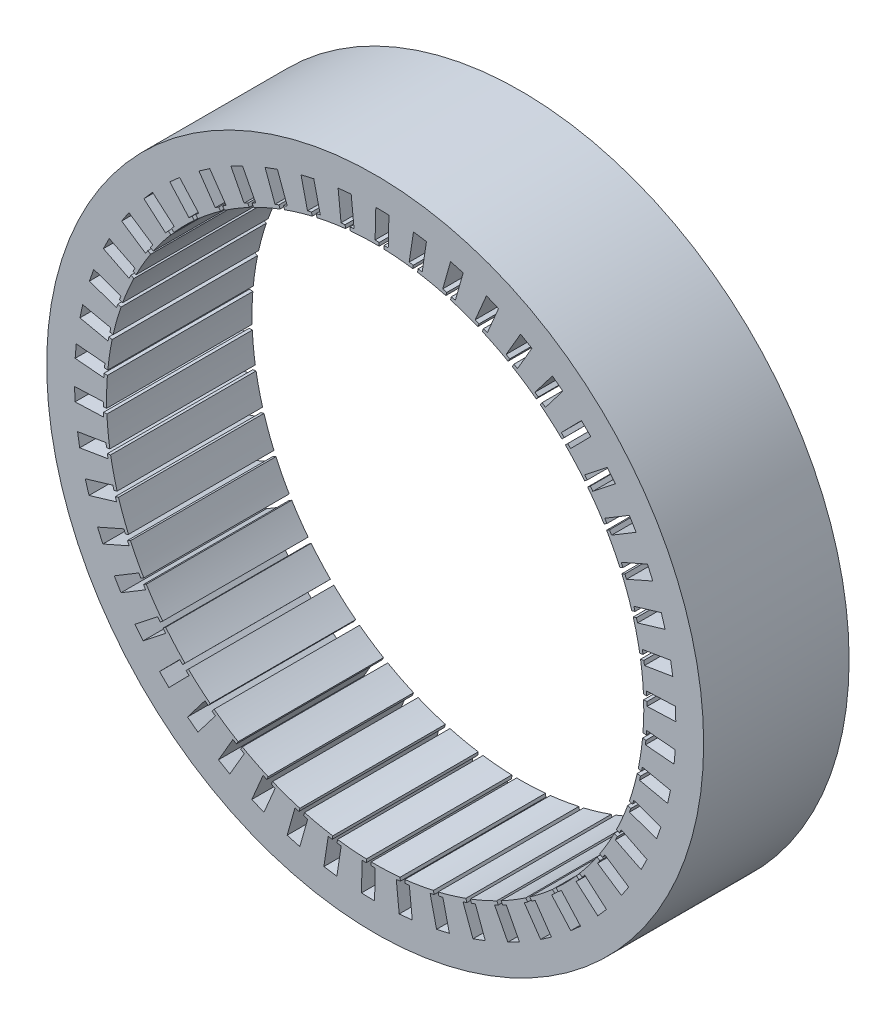
SolidWorks part; units mm, degrees
ref_plane "Спереди" through (0, 0, 0) normal (0, 0, 1) x (1, 0, 0)
ref_plane "Сверху" through (0, 0, 0) normal (0, 1, 0) x (1, 0, 0)
ref_plane "Справа" through (0, 0, 0) normal (1, 0, 0) x (0, 0, -1)
sketch "Эскиз1" plane through (0, 0, 0) normal (0, 0, 1) x (1, 0, 0)
  circle A0 centre (0, 0) radius 67.7538
  circle A1 centre (0, 0) radius 55.4
extrude "Rotor_stack" add sketch "Эскиз1" along normal blind 30 from offset 15
sketch "Эскиз2" plane through (0, 0, 0) normal (0, 0, 1) x (1, 0, 0)
  line L0 (54.5758, 1.6267) -> (56.0539, 1.6843)
  line L1 (56.0539, 1.6843) -> (56.0871, 0.8311)
  line L2 (56.0871, 0.8311) -> (62.0057, 1.0618)
  line L3 (62.0057, 1.0618) -> (61.9002, 3.7675)
  line L4 (61.9002, 3.7675) -> (55.9817, 3.5368)
  line L5 (55.9817, 3.5368) -> (56.0149, 2.6836)
  line L6 (56.0149, 2.6836) -> (54.5368, 2.626)
  line L7 (54.5368, 2.626) -> (54.5758, 1.6267)
  line L8 (53.9415, 8.4541) -> (55.4007, 8.6965)
  line L9 (55.4007, 8.6965) -> (55.5407, 7.8542)
  line L10 (55.5407, 7.8542) -> (61.3837, 8.8248)
  line L11 (61.3837, 8.8248) -> (60.9399, 11.4959)
  line L12 (60.9399, 11.4959) -> (55.0969, 10.5253)
  line L13 (55.0969, 10.5253) -> (55.2369, 9.683)
  line L14 (55.2369, 9.683) -> (53.7777, 9.4405)
  line L15 (53.7777, 9.4405) -> (53.9415, 8.4541)
  line L16 (52.4566, 15.1481) -> (53.8739, 15.5715)
  line L17 (53.8739, 15.5715) -> (54.1183, 14.7533)
  line L18 (54.1183, 14.7533) -> (59.7936, 16.4487)
  line L19 (59.7936, 16.4487) -> (59.0186, 19.0431)
  line L20 (59.0186, 19.0431) -> (53.3433, 17.3477)
  line L21 (53.3433, 17.3477) -> (53.5877, 16.5296)
  line L22 (53.5877, 16.5296) -> (52.1704, 16.1062)
  line L23 (52.1704, 16.1062) -> (52.4566, 15.1481)
  line L24 (50.1444, 21.6032) -> (51.4975, 22.2009)
  line L25 (51.4975, 22.2009) -> (51.8425, 21.4198)
  line L26 (51.8425, 21.4198) -> (57.2605, 23.8131)
  line L27 (57.2605, 23.8131) -> (56.1665, 26.2899)
  line L28 (56.1665, 26.2899) -> (50.7484, 23.8966)
  line L29 (50.7484, 23.8966) -> (51.0934, 23.1156)
  line L30 (51.0934, 23.1156) -> (49.7404, 22.5179)
  line L31 (49.7404, 22.5179) -> (50.1444, 21.6032)
  line L32 (47.0414, 27.7176) -> (48.3089, 28.4802)
  line L33 (48.3089, 28.4802) -> (48.7491, 27.7485)
  line L34 (48.7491, 27.7485) -> (53.8245, 30.802)
  line L35 (53.8245, 30.802) -> (52.4286, 33.1221)
  line L36 (52.4286, 33.1221) -> (47.3532, 30.0687)
  line L37 (47.3532, 30.0687) -> (47.7934, 29.337)
  line L38 (47.7934, 29.337) -> (46.5259, 28.5745)
  line L39 (46.5259, 28.5745) -> (47.0414, 27.7176)
  line L40 (43.1965, 33.3949) -> (44.3585, 34.3103)
  line L41 (44.3585, 34.3103) -> (44.8869, 33.6396)
  line L42 (44.8869, 33.6396) -> (49.5395, 37.3051)
  line L43 (49.5395, 37.3051) -> (47.8639, 39.432)
  line L44 (47.8639, 39.432) -> (43.2112, 35.7665)
  line L45 (43.2112, 35.7665) -> (43.7396, 35.0958)
  line L46 (43.7396, 35.0958) -> (42.5777, 34.1804)
  line L47 (42.5777, 34.1804) -> (43.1965, 33.3949)
  line L48 (38.6704, 38.5455) -> (39.7085, 39.5993)
  line L49 (39.7085, 39.5993) -> (40.3168, 39.0001)
  line L50 (40.3168, 39.0001) -> (44.4733, 43.2199)
  line L51 (44.4733, 43.2199) -> (42.5443, 45.12)
  line L52 (42.5443, 45.12) -> (38.3878, 40.9003)
  line L53 (38.3878, 40.9003) -> (38.9961, 40.3011)
  line L54 (38.9961, 40.3011) -> (37.958, 39.2473)
  line L55 (37.958, 39.2473) -> (38.6704, 38.5455)
  line L56 (33.5345, 43.0883) -> (34.4323, 44.2639)
  line L57 (34.4323, 44.2639) -> (35.1109, 43.7457)
  line L58 (35.1109, 43.7457) -> (38.7058, 48.453)
  line L59 (38.7058, 48.453) -> (36.5538, 50.0964)
  line L60 (36.5538, 50.0964) -> (32.9589, 45.389)
  line L61 (32.9589, 45.389) -> (33.6375, 44.8708)
  line L62 (33.6375, 44.8708) -> (32.7397, 43.6952)
  line L63 (32.7397, 43.6952) -> (33.5345, 43.0883)
  line L64 (27.8697, 46.9515) -> (28.613, 48.2303)
  line L65 (28.613, 48.2303) -> (29.3512, 47.8013)
  line L66 (29.3512, 47.8013) -> (32.3278, 52.9221)
  line L67 (32.3278, 52.9221) -> (29.9868, 54.2828)
  line L68 (29.9868, 54.2828) -> (27.0103, 49.162)
  line L69 (27.0103, 49.162) -> (27.7485, 48.7329)
  line L70 (27.7485, 48.7329) -> (27.0051, 47.454)
  line L71 (27.0051, 47.454) -> (27.8697, 46.9515)
  line L72 (21.7653, 50.0743) -> (22.3425, 51.4362)
  line L73 (22.3425, 51.4362) -> (23.1287, 51.103)
  line L74 (23.1287, 51.103) -> (25.44, 56.5565)
  line L75 (25.44, 56.5565) -> (22.9469, 57.6131)
  line L76 (22.9469, 57.6131) -> (20.6356, 52.1596)
  line L77 (20.6356, 52.1596) -> (21.4218, 51.8264)
  line L78 (21.4218, 51.8264) -> (20.8446, 50.4645)
  line L79 (20.8446, 50.4645) -> (21.7653, 50.0743)
  line L80 (15.3177, 52.4073) -> (15.7197, 53.8309)
  line L81 (15.7197, 53.8309) -> (16.5414, 53.5988)
  line L82 (16.5414, 53.5988) -> (18.151, 59.299)
  line L83 (18.151, 59.299) -> (15.5452, 60.0348)
  line L84 (15.5452, 60.0348) -> (13.9356, 54.3346)
  line L85 (13.9356, 54.3346) -> (14.7573, 54.1026)
  line L86 (14.7573, 54.1026) -> (14.3553, 52.6791)
  line L87 (14.3553, 52.6791) -> (15.3177, 52.4073)
  line L88 (8.6286, 53.9139) -> (8.8489, 55.3766)
  line L89 (8.8489, 55.3766) -> (9.6933, 55.2494)
  line L90 (9.6933, 55.2494) -> (10.5757, 61.1064)
  line L91 (10.5757, 61.1064) -> (7.8982, 61.5098)
  line L92 (7.8982, 61.5098) -> (7.0158, 55.6528)
  line L93 (7.0158, 55.6528) -> (7.8601, 55.5256)
  line L94 (7.8601, 55.5256) -> (7.6397, 54.0629)
  line L95 (7.6397, 54.0629) -> (8.6286, 53.9139)
  line L96 (1.8033, 54.5702) -> (1.8386, 56.049)
  line L97 (1.8386, 56.049) -> (2.6922, 56.0286)
  line L98 (2.6922, 56.0286) -> (2.8336, 61.95)
  line L99 (2.8336, 61.95) -> (0.1267, 62.0147)
  line L100 (0.1267, 62.0147) -> (-0.0147, 56.0933)
  line L101 (-0.0147, 56.0933) -> (0.8389, 56.0729)
  line L102 (0.8389, 56.0729) -> (0.8036, 54.5941)
  line L103 (0.8036, 54.5941) -> (1.8033, 54.5702)
  line L104 (-5.0504, 54.3659) -> (-5.2007, 55.8375)
  line L105 (-5.2007, 55.8375) -> (-4.3512, 55.9242)
  line L106 (-4.3512, 55.9242) -> (-4.9531, 61.8167)
  line L107 (-4.9531, 61.8167) -> (-7.6468, 61.5415)
  line L108 (-7.6468, 61.5415) -> (-7.0449, 55.6491)
  line L109 (-7.0449, 55.6491) -> (-6.1955, 55.7359)
  line L110 (-6.1955, 55.7359) -> (-6.0452, 54.2643)
  line L111 (-6.0452, 54.2643) -> (-5.0504, 54.3659)
  line L112 (-11.8244, 53.3043) -> (-12.158, 54.7454)
  line L113 (-12.158, 54.7454) -> (-11.3261, 54.9379)
  line L114 (-11.3261, 54.9379) -> (-12.6617, 60.7084)
  line L115 (-12.6617, 60.7084) -> (-15.2997, 60.0979)
  line L116 (-15.2997, 60.0979) -> (-13.9641, 54.3273)
  line L117 (-13.9641, 54.3273) -> (-13.1322, 54.5199)
  line L118 (-13.1322, 54.5199) -> (-12.7986, 53.0788)
  line L119 (-12.7986, 53.0788) -> (-11.8244, 53.3043)
  line L120 (-18.412, 51.4019) -> (-18.9235, 52.7899)
  line L121 (-18.9235, 52.7899) -> (-18.1223, 53.0852)
  line L122 (-18.1223, 53.0852) -> (-20.1707, 58.6428)
  line L123 (-20.1707, 58.6428) -> (-22.7113, 57.7064)
  line L124 (-22.7113, 57.7064) -> (-20.663, 52.1488)
  line L125 (-20.663, 52.1488) -> (-19.8618, 52.4441)
  line L126 (-19.8618, 52.4441) -> (-19.3503, 51.0561)
  line L127 (-19.3503, 51.0561) -> (-18.412, 51.4019)
  line L128 (-24.7091, 48.689) -> (-25.3906, 50.0019)
  line L129 (-25.3906, 50.0019) -> (-24.6328, 50.3952)
  line L130 (-24.6328, 50.3952) -> (-27.3615, 55.6523)
  line L131 (-27.3615, 55.6523) -> (-29.7647, 54.4049)
  line L132 (-29.7647, 54.4049) -> (-27.036, 49.1478)
  line L133 (-27.036, 49.1478) -> (-26.2782, 49.5412)
  line L134 (-26.2782, 49.5412) -> (-25.5967, 48.2283)
  line L135 (-25.5967, 48.2283) -> (-24.7091, 48.689)
  line L136 (-30.6167, 45.2082) -> (-31.4573, 46.4253)
  line L137 (-31.4573, 46.4253) -> (-30.7547, 46.9106)
  line L138 (-30.7547, 46.9106) -> (-34.1208, 51.7842)
  line L139 (-34.1208, 51.7842) -> (-36.3488, 50.2454)
  line L140 (-36.3488, 50.2454) -> (-32.9827, 45.3718)
  line L141 (-32.9827, 45.3718) -> (-32.2801, 45.857)
  line L142 (-32.2801, 45.857) -> (-31.4395, 44.6399)
  line L143 (-31.4395, 44.6399) -> (-30.6167, 45.2082)
  line L144 (-36.0413, 41.0144) -> (-37.0279, 42.1166)
  line L145 (-37.0279, 42.1166) -> (-36.3917, 42.6861)
  line L146 (-36.3917, 42.6861) -> (-40.3421, 47.0994)
  line L147 (-40.3421, 47.0994) -> (-42.3596, 45.2935)
  line L148 (-42.3596, 45.2935) -> (-38.4092, 40.8802)
  line L149 (-38.4092, 40.8802) -> (-37.773, 41.4496)
  line L150 (-37.773, 41.4496) -> (-36.7864, 40.3475)
  line L151 (-36.7864, 40.3475) -> (-36.0413, 41.0144)
  line L152 (-40.8976, 36.1738) -> (-42.0145, 37.1437)
  line L153 (-42.0145, 37.1437) -> (-41.4547, 37.7884)
  line L154 (-41.4547, 37.7884) -> (-45.9271, 41.6718)
  line L155 (-45.9271, 41.6718) -> (-47.7023, 39.6273)
  line L156 (-47.7023, 39.6273) -> (-43.23, 35.7439)
  line L157 (-43.23, 35.7439) -> (-42.6702, 36.3886)
  line L158 (-42.6702, 36.3886) -> (-41.5532, 35.4188)
  line L159 (-41.5532, 35.4188) -> (-40.8976, 36.1738)
  line L160 (-45.1089, 30.7628) -> (-46.3386, 31.585)
  line L161 (-46.3386, 31.585) -> (-45.864, 32.2948)
  line L162 (-45.864, 32.2948) -> (-50.7878, 35.587)
  line L163 (-50.7878, 35.587) -> (-52.2928, 33.3361)
  line L164 (-52.2928, 33.3361) -> (-47.369, 30.0439)
  line L165 (-47.369, 30.0439) -> (-46.8944, 30.7537)
  line L166 (-46.8944, 30.7537) -> (-45.6647, 29.9315)
  line L167 (-45.6647, 29.9315) -> (-45.1089, 30.7628)
  line L168 (-48.6088, 24.8666) -> (-49.9318, 25.5281)
  line L169 (-49.9318, 25.5281) -> (-49.5499, 26.2918)
  line L170 (-49.5499, 26.2918) -> (-54.8475, 28.941)
  line L171 (-54.8475, 28.941) -> (-56.0586, 26.5192)
  line L172 (-56.0586, 26.5192) -> (-50.761, 23.8701)
  line L173 (-50.761, 23.8701) -> (-50.3791, 24.6337)
  line L174 (-50.3791, 24.6337) -> (-49.0561, 23.9721)
  line L175 (-49.0561, 23.9721) -> (-48.6088, 24.8666)
  line L176 (-51.3421, 18.5782) -> (-52.7376, 19.0687)
  line L177 (-52.7376, 19.0687) -> (-52.4544, 19.8743)
  line L178 (-52.4544, 19.8743) -> (-58.0423, 21.8386)
  line L179 (-58.0423, 21.8386) -> (-58.9403, 19.2841)
  line L180 (-58.9403, 19.2841) -> (-53.3524, 17.3198)
  line L181 (-53.3524, 17.3198) -> (-53.0692, 18.1253)
  line L182 (-53.0692, 18.1253) -> (-51.6737, 17.6348)
  line L183 (-51.6737, 17.6348) -> (-51.3421, 18.5782)
  line L184 (-53.2657, 11.9968) -> (-54.7117, 12.3086)
  line L185 (-54.7117, 12.3086) -> (-54.5317, 13.1433)
  line L186 (-54.5317, 13.1433) -> (-60.3217, 14.3917)
  line L187 (-60.3217, 14.3917) -> (-60.8925, 11.7449)
  line L188 (-60.8925, 11.7449) -> (-55.1024, 10.4964)
  line L189 (-55.1024, 10.4964) -> (-54.9225, 11.3311)
  line L190 (-54.9225, 11.3311) -> (-53.4765, 11.0193)
  line L191 (-53.4765, 11.0193) -> (-53.2657, 11.9968)
  line L192 (-54.3493, 5.2262) -> (-55.823, 5.3543)
  line L193 (-55.823, 5.3543) -> (-55.749, 6.205)
  line L194 (-55.749, 6.205) -> (-61.6498, 6.7179)
  line L195 (-61.6498, 6.7179) -> (-61.8843, 4.0204)
  line L196 (-61.8843, 4.0204) -> (-55.9835, 3.5075)
  line L197 (-55.9835, 3.5075) -> (-55.9096, 4.3581)
  line L198 (-55.9096, 4.3581) -> (-54.4359, 4.23)
  line L199 (-54.4359, 4.23) -> (-54.3493, 5.2262)
  line L200 (-54.5758, -1.6267) -> (-56.0539, -1.6843)
  line L201 (-56.0539, -1.6843) -> (-56.0871, -0.8311)
  line L202 (-56.0871, -0.8311) -> (-62.0057, -1.0618)
  line L203 (-62.0057, -1.0618) -> (-61.9002, -3.7675)
  line L204 (-61.9002, -3.7675) -> (-55.9817, -3.5368)
  line L205 (-55.9817, -3.5368) -> (-56.0149, -2.6836)
  line L206 (-56.0149, -2.6836) -> (-54.5368, -2.626)
  line L207 (-54.5368, -2.626) -> (-54.5758, -1.6267)
  line L208 (-53.9415, -8.4541) -> (-55.4007, -8.6965)
  line L209 (-55.4007, -8.6965) -> (-55.5407, -7.8542)
  line L210 (-55.5407, -7.8542) -> (-61.3837, -8.8248)
  line L211 (-61.3837, -8.8248) -> (-60.9399, -11.4959)
  line L212 (-60.9399, -11.4959) -> (-55.0969, -10.5253)
  line L213 (-55.0969, -10.5253) -> (-55.2369, -9.683)
  line L214 (-55.2369, -9.683) -> (-53.7777, -9.4405)
  line L215 (-53.7777, -9.4405) -> (-53.9415, -8.4541)
  line L216 (-52.4566, -15.1481) -> (-53.8739, -15.5715)
  line L217 (-53.8739, -15.5715) -> (-54.1183, -14.7533)
  line L218 (-54.1183, -14.7533) -> (-59.7936, -16.4487)
  line L219 (-59.7936, -16.4487) -> (-59.0186, -19.0431)
  line L220 (-59.0186, -19.0431) -> (-53.3433, -17.3477)
  line L221 (-53.3433, -17.3477) -> (-53.5877, -16.5296)
  line L222 (-53.5877, -16.5296) -> (-52.1704, -16.1062)
  line L223 (-52.1704, -16.1062) -> (-52.4566, -15.1481)
  line L224 (-50.1444, -21.6032) -> (-51.4975, -22.2009)
  line L225 (-51.4975, -22.2009) -> (-51.8425, -21.4198)
  line L226 (-51.8425, -21.4198) -> (-57.2605, -23.8131)
  line L227 (-57.2605, -23.8131) -> (-56.1665, -26.2899)
  line L228 (-56.1665, -26.2899) -> (-50.7484, -23.8966)
  line L229 (-50.7484, -23.8966) -> (-51.0934, -23.1156)
  line L230 (-51.0934, -23.1156) -> (-49.7404, -22.5179)
  line L231 (-49.7404, -22.5179) -> (-50.1444, -21.6032)
  line L232 (-47.0414, -27.7176) -> (-48.3089, -28.4802)
  line L233 (-48.3089, -28.4802) -> (-48.7491, -27.7485)
  line L234 (-48.7491, -27.7485) -> (-53.8245, -30.802)
  line L235 (-53.8245, -30.802) -> (-52.4286, -33.1221)
  line L236 (-52.4286, -33.1221) -> (-47.3532, -30.0687)
  line L237 (-47.3532, -30.0687) -> (-47.7934, -29.337)
  line L238 (-47.7934, -29.337) -> (-46.5259, -28.5745)
  line L239 (-46.5259, -28.5745) -> (-47.0414, -27.7176)
  line L240 (-43.1965, -33.3949) -> (-44.3585, -34.3103)
  line L241 (-44.3585, -34.3103) -> (-44.8869, -33.6396)
  line L242 (-44.8869, -33.6396) -> (-49.5395, -37.3051)
  line L243 (-49.5395, -37.3051) -> (-47.8639, -39.432)
  line L244 (-47.8639, -39.432) -> (-43.2112, -35.7665)
  line L245 (-43.2112, -35.7665) -> (-43.7396, -35.0958)
  line L246 (-43.7396, -35.0958) -> (-42.5777, -34.1804)
  line L247 (-42.5777, -34.1804) -> (-43.1965, -33.3949)
  line L248 (-38.6704, -38.5455) -> (-39.7085, -39.5993)
  line L249 (-39.7085, -39.5993) -> (-40.3168, -39.0001)
  line L250 (-40.3168, -39.0001) -> (-44.4733, -43.2199)
  line L251 (-44.4733, -43.2199) -> (-42.5443, -45.12)
  line L252 (-42.5443, -45.12) -> (-38.3878, -40.9003)
  line L253 (-38.3878, -40.9003) -> (-38.9961, -40.3011)
  line L254 (-38.9961, -40.3011) -> (-37.958, -39.2473)
  line L255 (-37.958, -39.2473) -> (-38.6704, -38.5455)
  line L256 (-33.5345, -43.0883) -> (-34.4323, -44.2639)
  line L257 (-34.4323, -44.2639) -> (-35.1109, -43.7457)
  line L258 (-35.1109, -43.7457) -> (-38.7058, -48.453)
  line L259 (-38.7058, -48.453) -> (-36.5538, -50.0964)
  line L260 (-36.5538, -50.0964) -> (-32.9589, -45.389)
  line L261 (-32.9589, -45.389) -> (-33.6375, -44.8708)
  line L262 (-33.6375, -44.8708) -> (-32.7397, -43.6952)
  line L263 (-32.7397, -43.6952) -> (-33.5345, -43.0883)
  line L264 (-27.8697, -46.9515) -> (-28.613, -48.2303)
  line L265 (-28.613, -48.2303) -> (-29.3512, -47.8013)
  line L266 (-29.3512, -47.8013) -> (-32.3278, -52.9221)
  line L267 (-32.3278, -52.9221) -> (-29.9868, -54.2828)
  line L268 (-29.9868, -54.2828) -> (-27.0103, -49.162)
  line L269 (-27.0103, -49.162) -> (-27.7485, -48.7329)
  line L270 (-27.7485, -48.7329) -> (-27.0051, -47.454)
  line L271 (-27.0051, -47.454) -> (-27.8697, -46.9515)
  line L272 (-21.7653, -50.0743) -> (-22.3425, -51.4362)
  line L273 (-22.3425, -51.4362) -> (-23.1287, -51.103)
  line L274 (-23.1287, -51.103) -> (-25.44, -56.5565)
  line L275 (-25.44, -56.5565) -> (-22.9469, -57.6131)
  line L276 (-22.9469, -57.6131) -> (-20.6356, -52.1596)
  line L277 (-20.6356, -52.1596) -> (-21.4218, -51.8264)
  line L278 (-21.4218, -51.8264) -> (-20.8446, -50.4645)
  line L279 (-20.8446, -50.4645) -> (-21.7653, -50.0743)
  line L280 (-15.3177, -52.4073) -> (-15.7197, -53.8309)
  line L281 (-15.7197, -53.8309) -> (-16.5414, -53.5988)
  line L282 (-16.5414, -53.5988) -> (-18.151, -59.299)
  line L283 (-18.151, -59.299) -> (-15.5452, -60.0348)
  line L284 (-15.5452, -60.0348) -> (-13.9356, -54.3346)
  line L285 (-13.9356, -54.3346) -> (-14.7573, -54.1026)
  line L286 (-14.7573, -54.1026) -> (-14.3553, -52.6791)
  line L287 (-14.3553, -52.6791) -> (-15.3177, -52.4073)
  line L288 (-8.6286, -53.9139) -> (-8.8489, -55.3766)
  line L289 (-8.8489, -55.3766) -> (-9.6933, -55.2494)
  line L290 (-9.6933, -55.2494) -> (-10.5757, -61.1064)
  line L291 (-10.5757, -61.1064) -> (-7.8982, -61.5098)
  line L292 (-7.8982, -61.5098) -> (-7.0158, -55.6528)
  line L293 (-7.0158, -55.6528) -> (-7.8601, -55.5256)
  line L294 (-7.8601, -55.5256) -> (-7.6397, -54.0629)
  line L295 (-7.6397, -54.0629) -> (-8.6286, -53.9139)
  line L296 (-1.8033, -54.5702) -> (-1.8386, -56.049)
  line L297 (-1.8386, -56.049) -> (-2.6922, -56.0286)
  line L298 (-2.6922, -56.0286) -> (-2.8336, -61.95)
  line L299 (-2.8336, -61.95) -> (-0.1267, -62.0147)
  line L300 (-0.1267, -62.0147) -> (0.0147, -56.0933)
  line L301 (0.0147, -56.0933) -> (-0.8389, -56.0729)
  line L302 (-0.8389, -56.0729) -> (-0.8036, -54.5941)
  line L303 (-0.8036, -54.5941) -> (-1.8033, -54.5702)
  line L304 (5.0504, -54.3659) -> (5.2007, -55.8375)
  line L305 (5.2007, -55.8375) -> (4.3512, -55.9242)
  line L306 (4.3512, -55.9242) -> (4.9531, -61.8167)
  line L307 (4.9531, -61.8167) -> (7.6468, -61.5415)
  line L308 (7.6468, -61.5415) -> (7.0449, -55.6491)
  line L309 (7.0449, -55.6491) -> (6.1955, -55.7359)
  line L310 (6.1955, -55.7359) -> (6.0452, -54.2643)
  line L311 (6.0452, -54.2643) -> (5.0504, -54.3659)
  line L312 (11.8244, -53.3043) -> (12.158, -54.7454)
  line L313 (12.158, -54.7454) -> (11.3261, -54.9379)
  line L314 (11.3261, -54.9379) -> (12.6617, -60.7084)
  line L315 (12.6617, -60.7084) -> (15.2997, -60.0979)
  line L316 (15.2997, -60.0979) -> (13.9641, -54.3273)
  line L317 (13.9641, -54.3273) -> (13.1322, -54.5199)
  line L318 (13.1322, -54.5199) -> (12.7986, -53.0788)
  line L319 (12.7986, -53.0788) -> (11.8244, -53.3043)
  line L320 (18.412, -51.4019) -> (18.9235, -52.7899)
  line L321 (18.9235, -52.7899) -> (18.1223, -53.0852)
  line L322 (18.1223, -53.0852) -> (20.1707, -58.6428)
  line L323 (20.1707, -58.6428) -> (22.7113, -57.7064)
  line L324 (22.7113, -57.7064) -> (20.663, -52.1488)
  line L325 (20.663, -52.1488) -> (19.8618, -52.4441)
  line L326 (19.8618, -52.4441) -> (19.3503, -51.0561)
  line L327 (19.3503, -51.0561) -> (18.412, -51.4019)
  line L328 (24.7091, -48.689) -> (25.3906, -50.0019)
  line L329 (25.3906, -50.0019) -> (24.6328, -50.3952)
  line L330 (24.6328, -50.3952) -> (27.3615, -55.6523)
  line L331 (27.3615, -55.6523) -> (29.7647, -54.4049)
  line L332 (29.7647, -54.4049) -> (27.036, -49.1478)
  line L333 (27.036, -49.1478) -> (26.2782, -49.5412)
  line L334 (26.2782, -49.5412) -> (25.5967, -48.2283)
  line L335 (25.5967, -48.2283) -> (24.7091, -48.689)
  line L336 (30.6167, -45.2082) -> (31.4573, -46.4253)
  line L337 (31.4573, -46.4253) -> (30.7547, -46.9106)
  line L338 (30.7547, -46.9106) -> (34.1208, -51.7842)
  line L339 (34.1208, -51.7842) -> (36.3488, -50.2454)
  line L340 (36.3488, -50.2454) -> (32.9827, -45.3718)
  line L341 (32.9827, -45.3718) -> (32.2801, -45.857)
  line L342 (32.2801, -45.857) -> (31.4395, -44.6399)
  line L343 (31.4395, -44.6399) -> (30.6167, -45.2082)
  line L344 (36.0413, -41.0144) -> (37.0279, -42.1166)
  line L345 (37.0279, -42.1166) -> (36.3917, -42.6861)
  line L346 (36.3917, -42.6861) -> (40.3421, -47.0994)
  line L347 (40.3421, -47.0994) -> (42.3596, -45.2935)
  line L348 (42.3596, -45.2935) -> (38.4092, -40.8802)
  line L349 (38.4092, -40.8802) -> (37.773, -41.4496)
  line L350 (37.773, -41.4496) -> (36.7864, -40.3475)
  line L351 (36.7864, -40.3475) -> (36.0413, -41.0144)
  line L352 (40.8976, -36.1738) -> (42.0145, -37.1437)
  line L353 (42.0145, -37.1437) -> (41.4547, -37.7884)
  line L354 (41.4547, -37.7884) -> (45.9271, -41.6718)
  line L355 (45.9271, -41.6718) -> (47.7023, -39.6273)
  line L356 (47.7023, -39.6273) -> (43.23, -35.7439)
  line L357 (43.23, -35.7439) -> (42.6702, -36.3886)
  line L358 (42.6702, -36.3886) -> (41.5532, -35.4188)
  line L359 (41.5532, -35.4188) -> (40.8976, -36.1738)
  line L360 (45.1089, -30.7628) -> (46.3386, -31.585)
  line L361 (46.3386, -31.585) -> (45.864, -32.2948)
  line L362 (45.864, -32.2948) -> (50.7878, -35.587)
  line L363 (50.7878, -35.587) -> (52.2928, -33.3361)
  line L364 (52.2928, -33.3361) -> (47.369, -30.0439)
  line L365 (47.369, -30.0439) -> (46.8944, -30.7537)
  line L366 (46.8944, -30.7537) -> (45.6647, -29.9315)
  line L367 (45.6647, -29.9315) -> (45.1089, -30.7628)
  line L368 (48.6088, -24.8666) -> (49.9318, -25.5281)
  line L369 (49.9318, -25.5281) -> (49.5499, -26.2918)
  line L370 (49.5499, -26.2918) -> (54.8475, -28.941)
  line L371 (54.8475, -28.941) -> (56.0586, -26.5192)
  line L372 (56.0586, -26.5192) -> (50.761, -23.8701)
  line L373 (50.761, -23.8701) -> (50.3791, -24.6337)
  line L374 (50.3791, -24.6337) -> (49.0561, -23.9721)
  line L375 (49.0561, -23.9721) -> (48.6088, -24.8666)
  line L376 (51.3421, -18.5782) -> (52.7376, -19.0687)
  line L377 (52.7376, -19.0687) -> (52.4544, -19.8743)
  line L378 (52.4544, -19.8743) -> (58.0423, -21.8386)
  line L379 (58.0423, -21.8386) -> (58.9403, -19.2841)
  line L380 (58.9403, -19.2841) -> (53.3524, -17.3198)
  line L381 (53.3524, -17.3198) -> (53.0692, -18.1253)
  line L382 (53.0692, -18.1253) -> (51.6737, -17.6348)
  line L383 (51.6737, -17.6348) -> (51.3421, -18.5782)
  line L384 (53.2657, -11.9968) -> (54.7117, -12.3086)
  line L385 (54.7117, -12.3086) -> (54.5317, -13.1433)
  line L386 (54.5317, -13.1433) -> (60.3217, -14.3917)
  line L387 (60.3217, -14.3917) -> (60.8925, -11.7449)
  line L388 (60.8925, -11.7449) -> (55.1024, -10.4964)
  line L389 (55.1024, -10.4964) -> (54.9225, -11.3311)
  line L390 (54.9225, -11.3311) -> (53.4765, -11.0193)
  line L391 (53.4765, -11.0193) -> (53.2657, -11.9968)
  line L392 (54.3493, -5.2262) -> (55.823, -5.3543)
  line L393 (55.823, -5.3543) -> (55.749, -6.205)
  line L394 (55.749, -6.205) -> (61.6498, -6.7179)
  line L395 (61.6498, -6.7179) -> (61.8843, -4.0204)
  line L396 (61.8843, -4.0204) -> (55.9835, -3.5075)
  line L397 (55.9835, -3.5075) -> (55.9096, -4.3581)
  line L398 (55.9096, -4.3581) -> (54.4359, -4.23)
  line L399 (54.4359, -4.23) -> (54.3493, -5.2262)
extrude "Rotor_50_slots" cut sketch "Эскиз2" against normal mid plane 32
